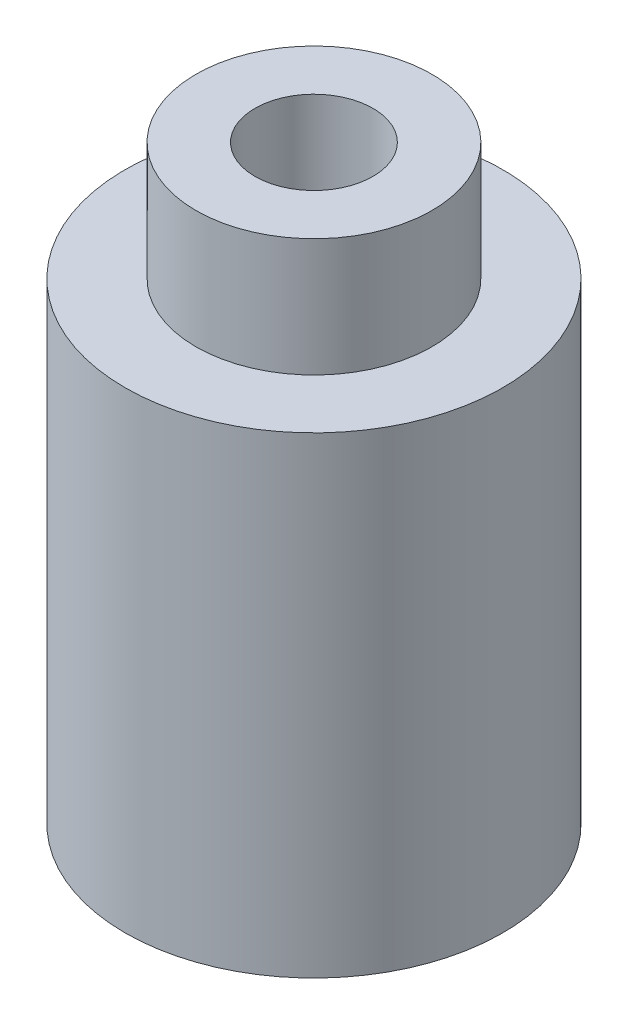
SolidWorks part; units mm, degrees
material "Polybutadiene (PB)"
ref_plane "Front Plane" through (0, 0, 0) normal (0, 0, 1) x (1, 0, 0)
ref_plane "Top Plane" through (0, 0, 0) normal (0, 1, 0) x (1, 0, 0)
ref_plane "Right Plane" through (0, 0, 0) normal (1, 0, 0) x (0, 0, -1)
sketch "Sketch1" plane through (0, 0, 0) normal (1, 0, 0) x (0, 0, -1)
  line L0 (1690.448, 1548.4252) -> (1687.948, 1548.4252)
  line L1 (1685.448, 1548.4252) -> (1685.448, 1543.4252)
  line L2 (1687.948, 1548.4252) -> (1687.948, 1542.0625)
  line L3 (1693.448, 1543.4252) -> (1690.448, 1543.4252)
  line L4 (1690.448, 1542.0625) -> (1687.948, 1542.0625)
  line L5 (1685.448, 1543.4252) -> (1685.448, 1523.4252)
  line L6 (1690.448, 1542.0625) -> (1690.448, 1523.4252)
  line L7 (1690.448, 1548.4252) -> (1690.448, 1543.4252)
  line L8 (1693.448, 1543.4252) -> (1693.448, 1523.4252)
  line L9 (1693.448, 1523.4252) -> (1690.448, 1523.4252)
  dimension "D1" = 2.5
  dimension "D2" = 5
  dimension "D3" = 2.5
  dimension "D4" = 3
  dimension "D5" = 5
revolve "Revolve1" add sketch "Sketch1" angle 360 about L5
